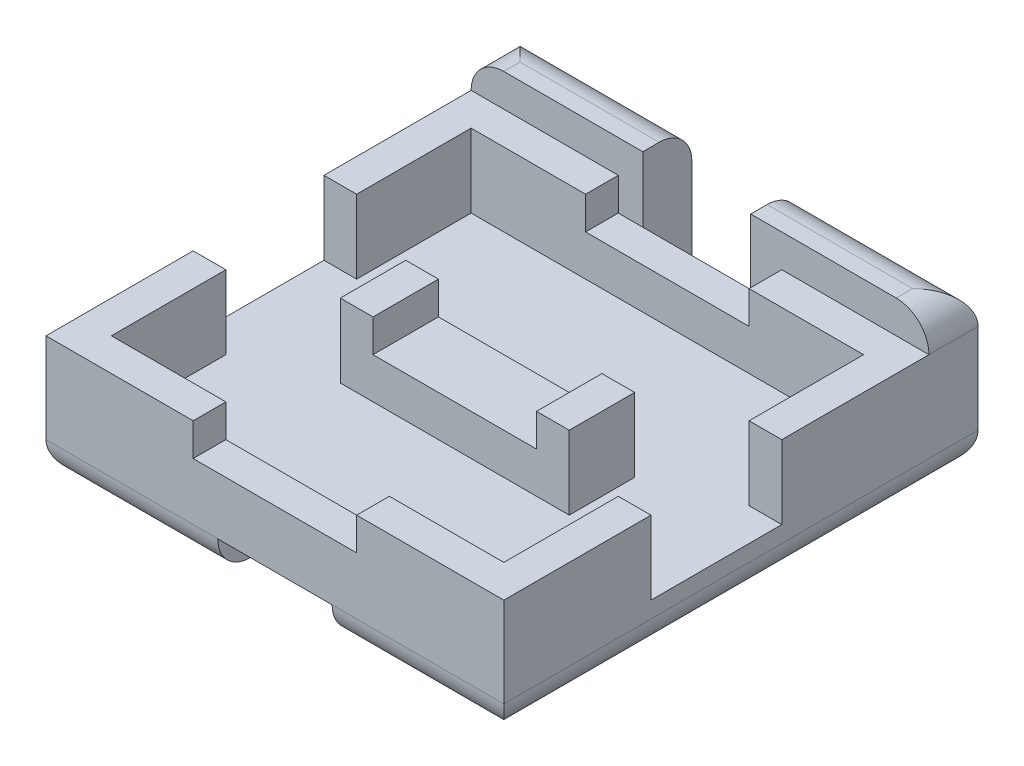
SolidWorks part; units mm, degrees
ref_plane "Front Plane" through (0, 0, 0) normal (0, 0, 1) x (1, 0, 0)
ref_plane "Top Plane" through (0, 0, 0) normal (0, 1, 0) x (1, 0, 0)
ref_plane "Right Plane" through (0, 0, 0) normal (1, 0, 0) x (0, 0, -1)
sketch "Sketch1" plane through (0, 0, 0) normal (0, 0, 1) x (1, 0, 0)
  line L0 (1.75, -12.6664) -> (7, -12.1039) construction
  line L1 (-7, -13.6039) -> (-1.75, -13.6039)
  line L2 (-7, -13.6039) -> (-7, -12.1039)
  line L3 (-6, -12.1039) -> (6.0004, -12.1039)
  line L4 (7, -13.6039) -> (7, -12.1039)
  line L5 (-7, -13.6039) -> (-1.75, -13.0414) construction
  line L6 (-7, -12.1039) -> (-1.75, -12.6664) construction
  line L8 (-1.75, -13.6039) -> (-1.75, -12.6039)
  line L9 (-1.75, -12.6039) -> (1.75, -12.6039)
  line L10 (1.75, -13.6039) -> (1.75, -12.6039)
  line L11 (1.75, -13.0414) -> (7, -13.6039) construction
  line L12 (1.75, -13.6039) -> (7, -13.6039)
  line L14 (-7, -12.1039) -> (-7, -9.8539)
  line L15 (-7, -9.8539) -> (-6, -9.8539)
  line L16 (-6, -12.1039) -> (-6, -9.8539)
  line L18 (7, -12.1039) -> (7, -9.8539)
  line L19 (7, -9.8539) -> (6.0004, -9.8539)
  line L20 (6.0004, -12.1039) -> (6.0004, -9.8539)
  point P0 (0, -12.8539)
  dimension "D1" = 14
  dimension "D2" = 1.5
  dimension "D3" = 1
  dimension "D4" = 3.5
  dimension "D5" = 1.75
  dimension "D6" = 1
  dimension "D7" = 2.25
  dimension "D8" = 0.9996
  dimension "D9" = 2.25
  dimension "D10" = 1.5
  dimension "D11" = 1.75
extrude "Boss-Extrude1" add sketch "Sketch1" along normal blind 13
sketch "Sketch2" plane through (0, -12.1039, 0) normal (0, 1, 0) x (1, 0, 0)
  line L0 (6.0004, -13) -> (6.0004, 0) construction
  line L1 (-6, 0) -> (6.0004, 0)
  line L2 (-6, 0) -> (-6, -1)
  line L3 (-6, -1) -> (6.0004, -1)
  line L4 (6.0004, 0) -> (6.0004, -1)
  line L5 (6.0004, -13) -> (6.0004, 0) construction
  line L6 (-6, -13) -> (6.0004, -13)
  line L7 (-6, -13) -> (-6, -12)
  line L8 (-6, -12) -> (6.0004, -12)
  line L9 (6.0004, -13) -> (6.0004, -12)
  dimension "D1" = 1
  dimension "D2" = 1
extrude "Boss-Extrude2" add sketch "Sketch2" along normal up to surface (2.25 mm away) up to face at (-6.5, -9.8539, 6.5)
sketch "Sketch5" plane through (-7, 0, 0) normal (-1, 0, 0) x (0, 0, 1)
  line L0 (13, -9.8539) -> (0, -9.8539) construction
  line L1 (4.5, -9.8539) -> (8.5, -9.8539)
  line L2 (4.5, -9.8539) -> (4.5, -12.1039)
  line L3 (4.5, -12.1039) -> (8.5, -12.1039)
  line L4 (8.5, -9.8539) -> (8.5, -12.1039)
  line L5 (12, -12.1039) -> (1, -12.1039) construction
  line L6 (1, -9.8539) -> (1, -12.1039) construction
  line L7 (12, -9.8539) -> (12, -12.1039) construction
  dimension "D1" = 4
  dimension "D2" = 3.5
  dimension "D3" = 3.5
extrude "Cut-Extrude2" cut sketch "Sketch5" against normal up to surface (14 mm away) up to face at (7, -11.7289, 6.5)
sketch "Sketch6" plane through (0, -12.1039, 0) normal (0, 1, 0) x (1, 0, 0)
  line L0 (-7, -4.5) -> (-7, -8.5) construction
  line L1 (3.5, -7.5) -> (-3.5, -7.5)
  line L2 (3.5, -7.5) -> (3.5, -5.5)
  line L3 (3.5, -5.5) -> (-3.5, -5.5)
  line L4 (-3.5, -7.5) -> (-3.5, -5.5)
  line L5 (3.5, -7.5) -> (-3.5, -5.5) construction
  line L6 (3.5, -5.5) -> (-3.5, -7.5) construction
  line L7 (7, -8.5) -> (7, -4.5) construction
  line L8 (7, -8.5) -> (6.0004, -8.5) construction
  line L9 (7, -4.5) -> (6.0004, -4.5) construction
  point P0 (0, -6.5)
  point P11 (6.5002, -4.5)
  dimension "D1" = 3.5
  dimension "D2" = 3.5
  dimension "D3" = 1
  dimension "D4" = 1
extrude "Boss-Extrude4" add sketch "Sketch6" along normal up to surface (2.25 mm away) up to face at (0.0001, -9.8539, 2.5)
sketch "Sketch4" plane through (0, 0, 0) normal (0, 0, -1) x (-1, 0, 0)
  line L0 (-7, -9.8539) -> (7, -9.8539) construction
  line L1 (-2.5, -9.8539) -> (2.5, -9.8539)
  line L2 (-2.5, -9.8539) -> (-2.5, -10.8539)
  line L3 (-2.5, -10.8539) -> (2.5, -10.8539)
  line L4 (2.5, -9.8539) -> (2.5, -10.8539)
  line L5 (-1.75, -12.6039) -> (-1.75, -13.6039) construction
  line L6 (1.75, -13.6039) -> (1.75, -12.6039) construction
  dimension "D1" = 1
  dimension "D2" = 0.75
  dimension "D3" = 0.75
  dimension "D4" = 5
extrude "Cut-Extrude1" cut sketch "Sketch4" against normal through all
sketch "Sketch7" plane through (0, 0, 0) normal (0, 0, -1) x (-1, 0, 0)
  line L1 (1.75, -13.6039) -> (7, -13.6039)
  line L2 (1.75, -13.6039) -> (1.75, -8.8539)
  line L3 (1.75, -8.8539) -> (7, -8.8539)
  line L4 (7, -13.6039) -> (7, -8.8539)
  line L5 (-7, -13.6039) -> (-1.55, -13.6039)
  line L6 (-7, -13.6039) -> (-7, -8.8539)
  line L7 (-7, -8.8539) -> (-1.55, -8.8539)
  line L8 (-1.55, -13.6039) -> (-1.55, -8.8539)
  dimension "D1" = 4.75
  dimension "D2" = 4.75
extrude "Boss-Extrude5" add sketch "Sketch7" along normal blind 1.5
fillet "Fillet5" radius 1 6 edges at (4.375, -13.6039, 13) (-4.375, -13.6039, -1.5) (-4.375, -13.6039, 13) (-7, -13.6039, 5.75) (7, -13.6039, 5.75) (4.275, -13.6039, -1.5)
fillet "Fillet6" radius 1 4 edges at (-7, -8.8539, -0.75) (7, -8.8539, -0.75) (-4.375, -8.8539, -1.5) (4.275, -8.8539, -1.5)
